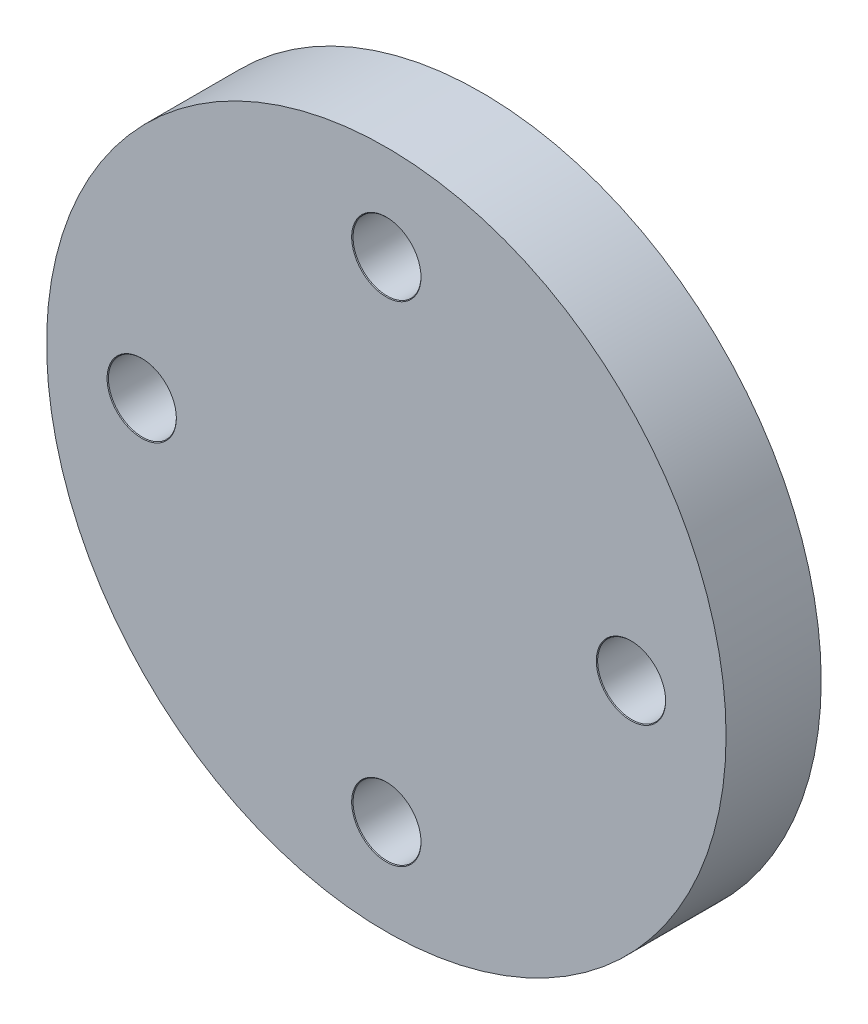
SolidWorks part; units mm, degrees
material "6061 Alloy"
ref_plane "Front Plane" through (0, 0, 0) normal (0, 0, 1) x (1, 0, 0)
ref_plane "Top Plane" through (0, 0, 0) normal (0, 1, 0) x (1, 0, 0)
ref_plane "Right Plane" through (0, 0, 0) normal (1, 0, 0) x (0, 0, -1)
sketch "Sketch1" plane through (0, 0, 0) normal (0, 0, 1) x (1, 0, 0)
  circle A0 centre (0, 0) radius 2.5
  circle A2 centre (0, 0) radius 4
  dimension "D1" = 5
  dimension "D2" = 8
extrude "Boss-Extrude1" add sketch "Sketch1" against normal blind 5
sketch "Sketch2" plane through (0, 0, 0) normal (0, 0, 1) x (1, 0, 0)
  circle A0 centre (0, 0) radius 12.5
  circle A1 centre (0, 0) radius 2.5
  circle A2 centre (0, 0) radius 2.5 construction
  dimension "D1" = 25
extrude "Boss-Extrude2" add sketch "Sketch2" along normal blind 3.5
hole_wizard "Tap Drill for M3 Tap1" positions "3DSketch2" profile "Sketch6" hole size "M3" standard "GB"
sketch3d "3DSketch2"
  point P0 (4, 0, -2.5)
  dimension "D1" = 2.5
sketch "Sketch6" plane through (4, 0, -2.5) normal (0, 1, 0) x (0, 0, -1)
  line L0 (0, 0) -> (0, 5.7511)
  line L1 (0, 5.7511) -> (1.25, 5)
  line L2 (1.25, 5) -> (1.25, 0.025)
  line L3 (1.25, 0.025) -> (1.275, 0)
  line L5 (1.275, 0) -> (0, 0)
  line L6 (-1.25, 0.025) -> (-1.275, 0) construction
  line L10 (0, 5.7511) -> (-1.25, 5) construction
  line L11 (0, -6.35) -> (0, 107.95) construction
  dimension "Hole Dia." = 2.5
  dimension "Hole Depth" = 5
  dimension "Near C'Sink Dia." = 2.55
  dimension "Near C'Sink Angle" = 90
  dimension "Drill Angle" = 118
sketch "Sketch7" plane through (0, 0, 3.5) normal (0, 0, 1) x (1, 0, 0)
  line L0 (4.675, 0) -> (-4.675, 0) construction
  point P0 (-9, 0)
  dimension "D1" = 9
hole_wizard "Tap Drill for M3 Tap2" positions "3DSketch3" profile "Sketch8" hole size "M3" standard "GB"
sketch3d "3DSketch3"
  point P0 (-9, 0, 3.5)
sketch "Sketch8" plane through (-9, 0, 3.5) normal (1, 0, 0) x (0, -1, 0)
  line L0 (0, 0) -> (0, 5.7511)
  line L1 (0, 5.7511) -> (1.25, 5)
  line L2 (1.25, 5) -> (1.25, 0.025)
  line L3 (1.25, 0.025) -> (1.275, 0)
  line L5 (1.275, 0) -> (0, 0)
  line L6 (-1.25, 0.025) -> (-1.275, 0) construction
  line L10 (0, 5.7511) -> (-1.25, 5) construction
  line L11 (0, -6.35) -> (0, 107.95) construction
  dimension "Hole Dia." = 2.5
  dimension "Hole Depth" = 5
  dimension "Near C'Sink Dia." = 2.55
  dimension "Near C'Sink Angle" = 90
  dimension "Drill Angle" = 118
pattern_circular "CirPattern1" count 4 every 90 of "Tap Drill for M3 Tap2"
pattern_circular "CirPattern2" count 4 every 90 of "Tap Drill for M3 Tap1"
chamfer "Chamfer1" distance 0.5 angle 45
sketch "Sketch9" plane through (0, 0, 3.5) normal (0, 0, 1) x (1, 0, 0)
  circle A0 centre (0, 0) radius 2.5
extrude "Boss-Extrude3" add sketch "Sketch9" against normal blind 2.9
